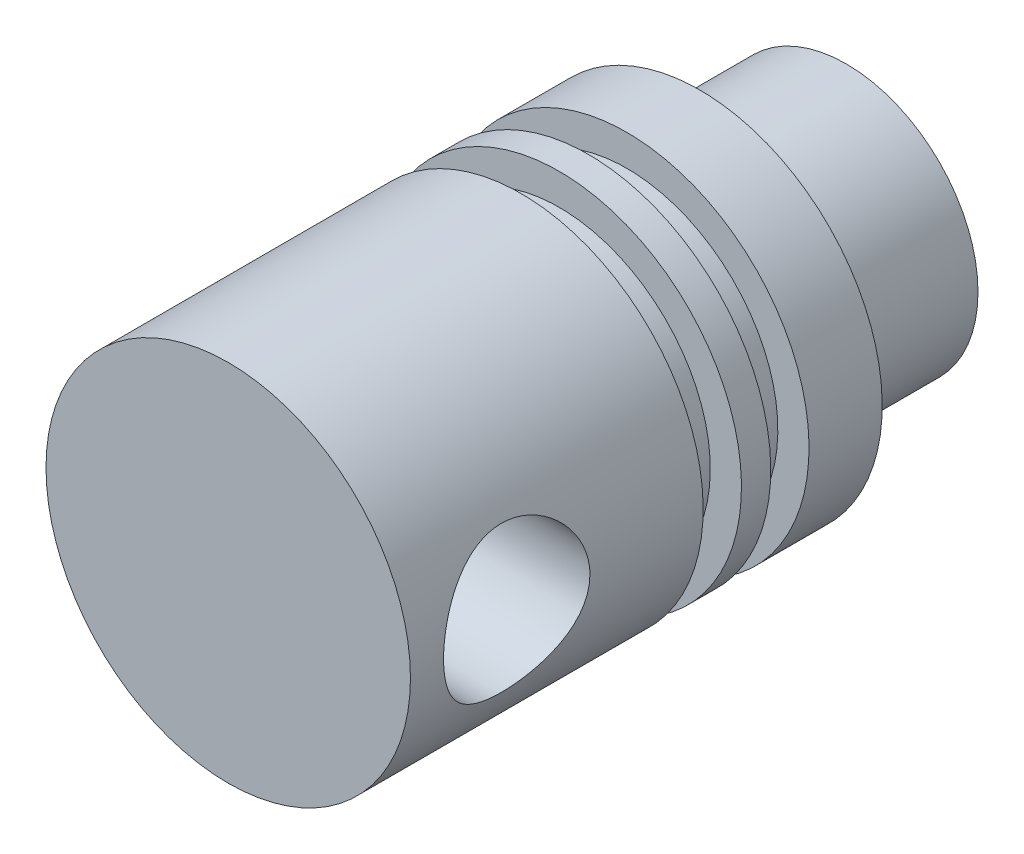
SolidWorks part; units mm, degrees
ref_plane "Front Plane" through (0, 0, 0) normal (0, 0, 1) x (1, 0, 0)
ref_plane "Top Plane" through (0, 0, 0) normal (0, 1, 0) x (1, 0, 0)
ref_plane "Right Plane" through (0, 0, 0) normal (1, 0, 0) x (0, 0, -1)
sketch "Sketch2" plane through (0, 0, 0) normal (1, 0, 0) x (0, 0, -1)
  line L0 (0, 0) -> (0, 12.45)
  line L1 (0, 12.45) -> (-5, 12.45)
  line L2 (-5, 12.45) -> (-5, 10.32)
  line L3 (-5, 10.32) -> (-7.6162, 10.32)
  line L4 (-7.6162, 10.32) -> (-7.6162, 12.45)
  line L5 (-7.6162, 12.45) -> (-9.6162, 12.45)
  line L6 (-9.6162, 12.45) -> (-9.6162, 10.32)
  line L7 (-9.6162, 10.32) -> (-12.2324, 10.32)
  line L8 (-12.2324, 10.32) -> (-12.2324, 12.45)
  line L9 (-12.2324, 12.45) -> (-17.2324, 12.45)
  line L10 (-17.2324, 12.45) -> (-17.2324, 0)
  line L11 (-17.2324, 0) -> (0, 0)
  dimension "D1" = 12.45
  dimension "D2" = 2.6162
  dimension "D3" = 2.6162
  dimension "D4" = 2
  dimension "D5" = 5
  dimension "D6" = 10.32
  dimension "D7" = 5
revolve "Revolve1" add sketch "Sketch2" angle 360 about L11
sketch "Sketch3" plane through (0, 0, 0) normal (0, 0, -1) x (-1, 0, 0)
  line L0 (0, -2.232) -> (0, 3.8523) construction
  circle A0 centre (0, 0) radius 8.9949
  circle A1 centre (0, 0) radius 5.9949
  dimension "D1" = 11.9898
  dimension "D2" = 3
extrude "Boss-Extrude4" add sketch "Sketch3" along normal blind 10 contours A0 | A1
sketch "Sketch4" plane through (0, 0, 17.2324) normal (0, 0, 1) x (1, 0, 0)
  circle A1 centre (0, 0) radius 12.45
  circle A2 centre (0, 0) radius 12.45
  dimension "D1" = 0
extrude "Boss-Extrude5" add sketch "Sketch4" along normal blind 15
sketch "Sketch5" plane through (0, 0, 0) normal (1, 0, 0) x (0, 0, -1)
  circle A0 centre (-24.9689, 0) radius 5
  point P2 (-21.8359, 0)
  point P3 (-24.9689, 0)
  dimension "D1" = 10
extrude "Cut-Extrude1" cut sketch "Sketch5" against normal through all both and the other way through all contours A0
